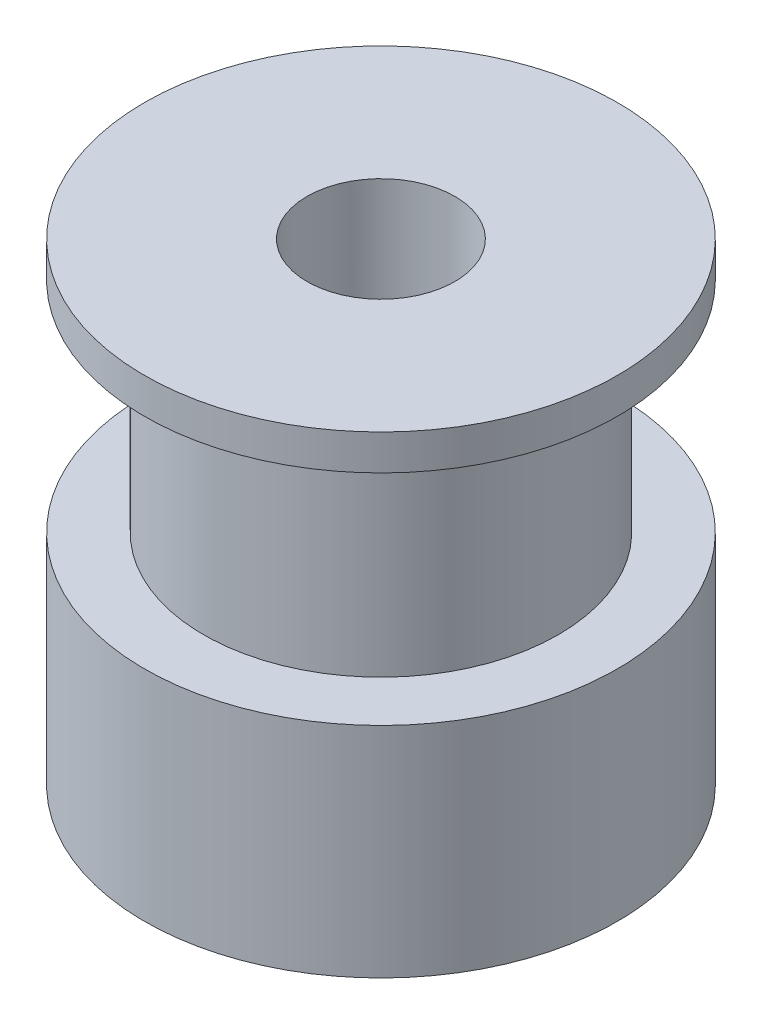
SolidWorks part; units mm, degrees
ref_plane "Front Plane" through (0, 0, 0) normal (0, 0, 1) x (1, 0, 0)
ref_plane "Top Plane" through (0, 0, 0) normal (0, 1, 0) x (1, 0, 0)
ref_plane "Right Plane" through (0, 0, 0) normal (1, 0, 0) x (0, 0, -1)
sketch "Sketch1" plane through (0, 0, 0) normal (0, 0, 1) x (1, 0, 0)
  line L0 (0, 1004.7764) -> (0, 5) construction
  line L1 (0, -11) -> (0, -1018.6139) construction
  line L2 (0, 5) -> (-8, 5)
  line L4 (-6, 3.8) -> (-8, 3.8)
  line L5 (-8, 5) -> (-8, 3.8)
  line L7 (-6, 3.8) -> (-6, -3.6)
  line L10 (-6, -3.6) -> (-8, -3.6)
  line L12 (0, -11) -> (-8, -11)
  line L13 (-8, -3.6) -> (-8, -11)
  line L14 (0, 5) -> (0, -11)
  dimension "D1" = 7.4
  dimension "D2" = 16
  dimension "D3" = 7.4
  dimension "D4" = 8
  dimension "D5" = 8
  dimension "D6" = 6
  dimension "D7" = 5
revolve "Revolve1" add sketch "Sketch1" angle 360 about L0
sketch "Sketch2" plane through (0, 5, 0) normal (0, 1, 0) x (1, 0, 0)
  circle A0 centre (0, 0) radius 2.5
  dimension "D1" = 5
extrude "Cut-Extrude1" cut sketch "Sketch2" against normal up to next
sketch "Sketch3" plane through (0, 0, 0) normal (0, 0, 1) x (1, 0, 0)
  line L0 (0, 0) -> (0, -6.4964) construction
  line L1 (8, -3.6) -> (-8, -3.6) construction
  circle A0 centre (0, -7.3) radius 2
  dimension "D1" = 4
  dimension "D2" = 3.7
extrude "Cut-Extrude2" cut sketch "Sketch3" against normal up to next
pattern_circular "CirPattern1" count 2 every 90 about axis through (0, -11, 0) along (0, -1, 0) of "Cut-Extrude2"
